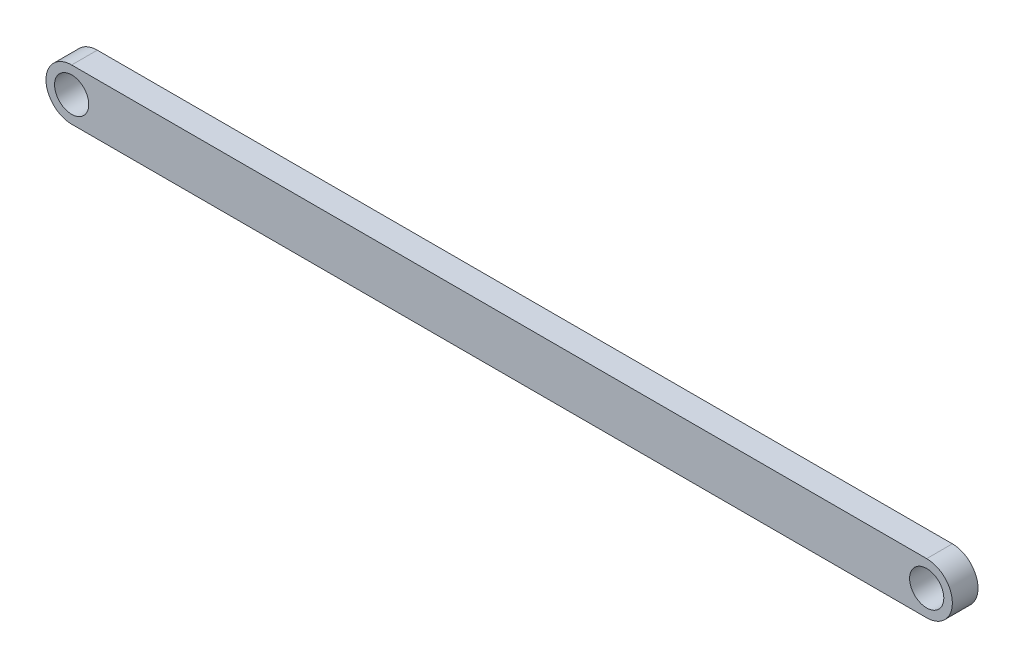
SolidWorks part; units mm, degrees
ref_plane "Front Plane" through (0, 0, 0) normal (0, 0, 1) x (1, 0, 0)
ref_plane "Top Plane" through (0, 0, 0) normal (0, 1, 0) x (1, 0, 0)
ref_plane "Right Plane" through (0, 0, 0) normal (1, 0, 0) x (0, 0, -1)
sketch "Sketch1" plane through (0, 0, 0) normal (0, 0, 1) x (1, 0, 0)
  line L0 (-500, 15) -> (0, 15)
  line L1 (-500, -15) -> (0, -15)
  circle A0 centre (-500, 0) radius 10
  circle A1 centre (0, 0) radius 10
  arc A2 (-500, -15) -> (-500, 15) centre (-500, 0) cw
  arc A3 (0, -15) -> (0, 15) centre (0, 0) ccw
  dimension "D1" = 500
  dimension "D3" = 20
  dimension "D2" = 30
extrude "Extrude1" add sketch "Sketch1" along normal blind 15
